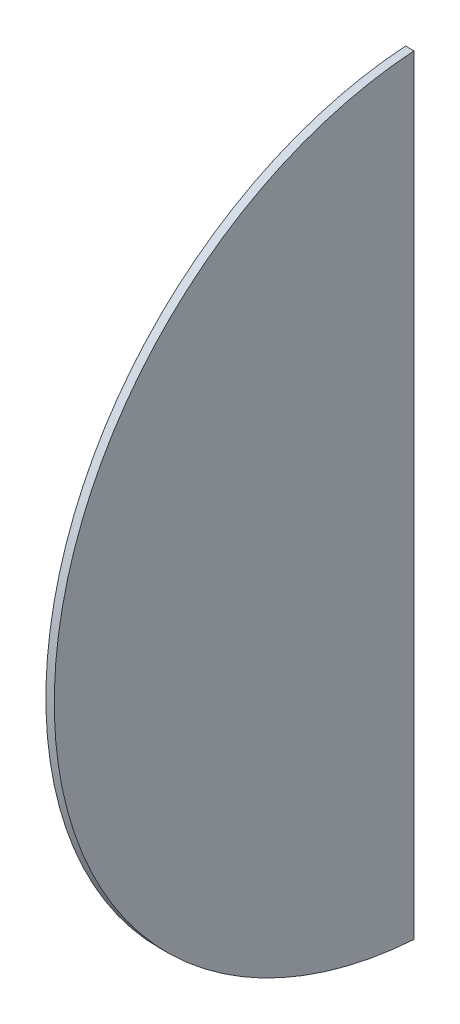
SolidWorks part; units mm, degrees
material "White Painted Steel"
ref_plane "Front Plane" through (0, 0, 0) normal (1, 0, 0) x (0, 1, 0)
ref_plane "Top Plane" through (0, 0, 0) normal (0, 0, 1) x (0, 1, 0)
ref_plane "Right Plane" through (0, 0, 0) normal (0, 1, 0) x (-1, 0, 0)
sketch "Sketch1" plane through (0, 0, 0) normal (1, 0, 0) x (0, 1, 0)
  line L0 (-460, 0) -> (460, 0)
  arc A0 (-460, 0) -> (460, 0) centre (0, -31.0465) cw
  point P3 (-11.6139, -32.2686)
  point P4 (0, 0)
  point P6 (0, 0)
  point P8 (0, 430)
  point P9 (0, 0)
  point P10 (0, 0)
  dimension "D2" = 430
  dimension "D1" = 920
extrude "Boss-Extrude1" add sketch "Sketch1" along normal blind 10
